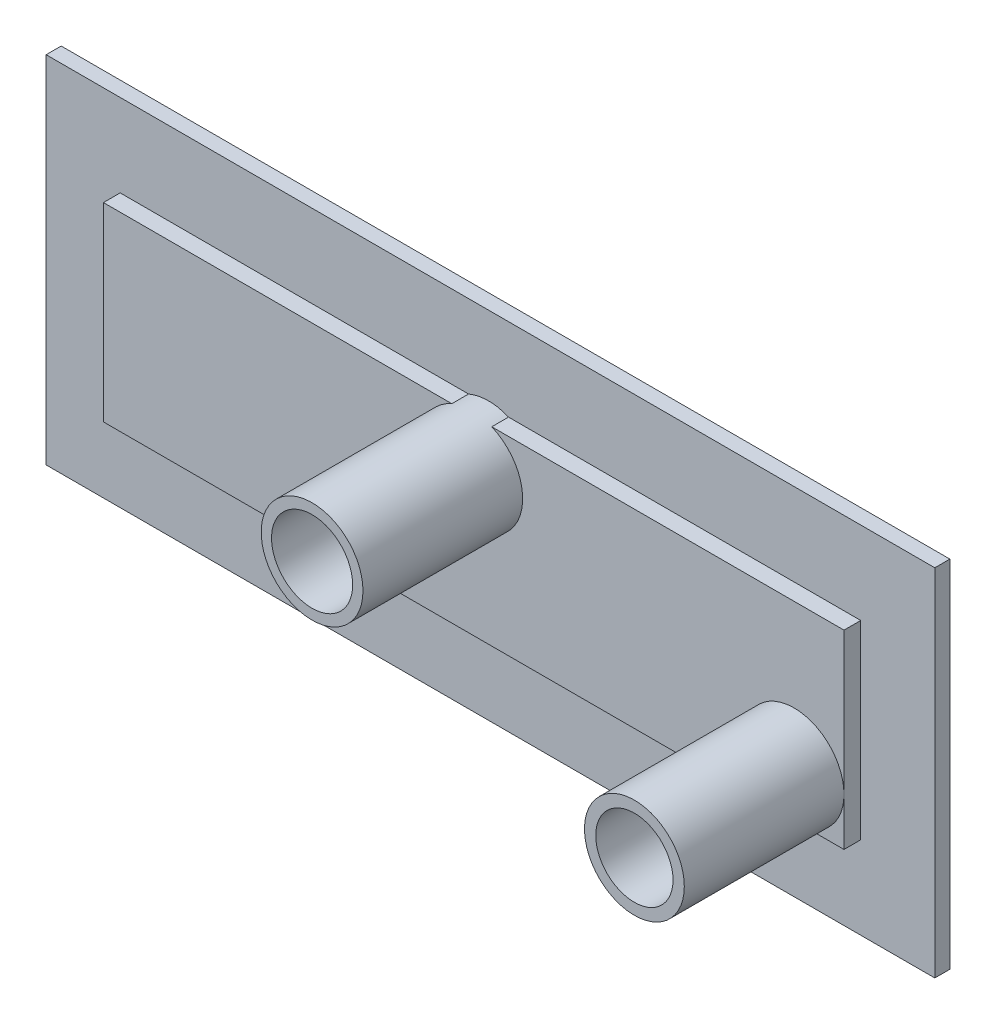
SolidWorks part; units mm, degrees
material "ABS"
ref_plane "X-Y Datum" through (0, 0, 0) normal (0, 0, 1) x (1, 0, 0)
ref_plane "X-Z Datum" through (0, 0, 0) normal (0, 1, 0) x (1, 0, 0)
ref_plane "Y-Z Datum" through (0, 0, 0) normal (1, 0, 0) x (0, 0, -1)
sketch "Sketch1" plane through (0, 0, 0) normal (0, 0, 1) x (1, 0, 0)
  line L2 (-87.63, 35.0329) -> (87.63, 35.033)
  line L3 (-87.63, 35.0329) -> (-87.63, 0)
  line L5 (87.63, 35.033) -> (87.63, 0)
  line L6 (87.63, 0) -> (87.63, -35.0329)
  line L7 (87.63, -35.0329) -> (0, -35.0329)
  line L8 (0, -35.0329) -> (-87.63, -35.0329)
  line L9 (-87.63, -35.0329) -> (-87.63, 0)
  point P8 (0, 35.0329)
extrude "Boss-Extrude1" add sketch "Sketch1" along normal blind 2.9718
sketch "Sketch2" plane through (0, 0, 2.9718) normal (0, 0, 1) x (1, 0, 0)
  line L1 (-73.025, 18.7325) -> (73.025, 18.7325)
  line L2 (73.025, 18.7325) -> (73.025, 0)
  line L4 (73.025, 0) -> (73.025, -18.7325)
  line L5 (-73.025, 18.7325) -> (-73.025, 0)
  line L6 (-73.025, 0) -> (-73.025, -18.7325)
  line L7 (-73.025, -18.7325) -> (0, -18.7325)
  line L8 (0, -18.7325) -> (73.025, -18.7325)
  point P6 (0, 18.7325)
extrude "Boss-Extrude2" add sketch "Sketch2" along normal blind 3.302
sketch "Sketch3" plane through (0, 0, 0) normal (0, 0, -1) x (-1, 0, 0)
  line L1 (-75.438, 21.209) -> (75.438, 21.209)
  line L2 (75.438, 21.209) -> (75.438, 0)
  line L4 (75.438, 0) -> (75.438, -21.209)
  line L5 (75.438, -21.209) -> (0, -21.209)
  line L6 (0, -21.209) -> (-75.438, -21.209)
  line L7 (-75.438, -21.209) -> (-75.438, 0)
  line L8 (-75.438, 0) -> (-75.438, 21.209)
  point P6 (0, 21.209)
extrude "Boss-Extrude3" add sketch "Sketch3" along normal blind 10.668
sketch "Sketch4" plane through (0, 0, 2.9718) normal (0, 0, 1) x (1, 0, 0)
  line L0 (87.63, -35.0329) -> (87.63, -9.3155)
  line L2 (-87.63, -35.0329) -> (87.63, -35.0329) construction
  line L3 (87.63, -9.3155) -> (73.025, -9.3155)
  line L4 (87.63, -35.0329) -> (87.63, 35.033) construction
  line L6 (73.025, -18.7325) -> (73.025, 18.7325) construction
  line L7 (63.1825, -35.0329) -> (63.1825, -19.1579)
  circle A0 centre (63.1825, -9.3155) radius 9.8425
sketch "Sketch5" plane through (0, 0, 2.9718) normal (0, 0, 1) x (1, 0, 0)
  line L0 (87.63, 35.033) -> (87.63, 9.506)
  line L1 (87.63, -35.0329) -> (87.63, 35.033) construction
  line L2 (87.63, 35.033) -> (-0.381, 35.033)
  line L3 (87.63, 35.033) -> (-87.63, 35.0329) construction
  line L4 (-0.381, 35.033) -> (-0.381, 9.506)
  circle A0 centre (-0.381, 9.506) radius 10.033
extrude "Boss-Extrude4" add sketch "Sketch5" along normal blind 34.798 contours A0
extrude "Boss-Extrude5" add sketch "Sketch4" along normal blind 34.798 contours A0
sketch "Sketch6" plane through (0, 0, 37.7698) normal (0, 0, 1) x (1, 0, 0)
  circle A0 centre (63.1825, -9.3155) radius 7.62
  circle A1 centre (-0.381, 9.506) radius 8.001
extrude "Cut-Extrude1" cut sketch "Sketch6" against normal through all both and the other way through all
sketch "Sketch7" plane through (0, 0, -10.668) normal (0, 0, -1) x (-1, 0, 0)
  point P0 (0, 0)
